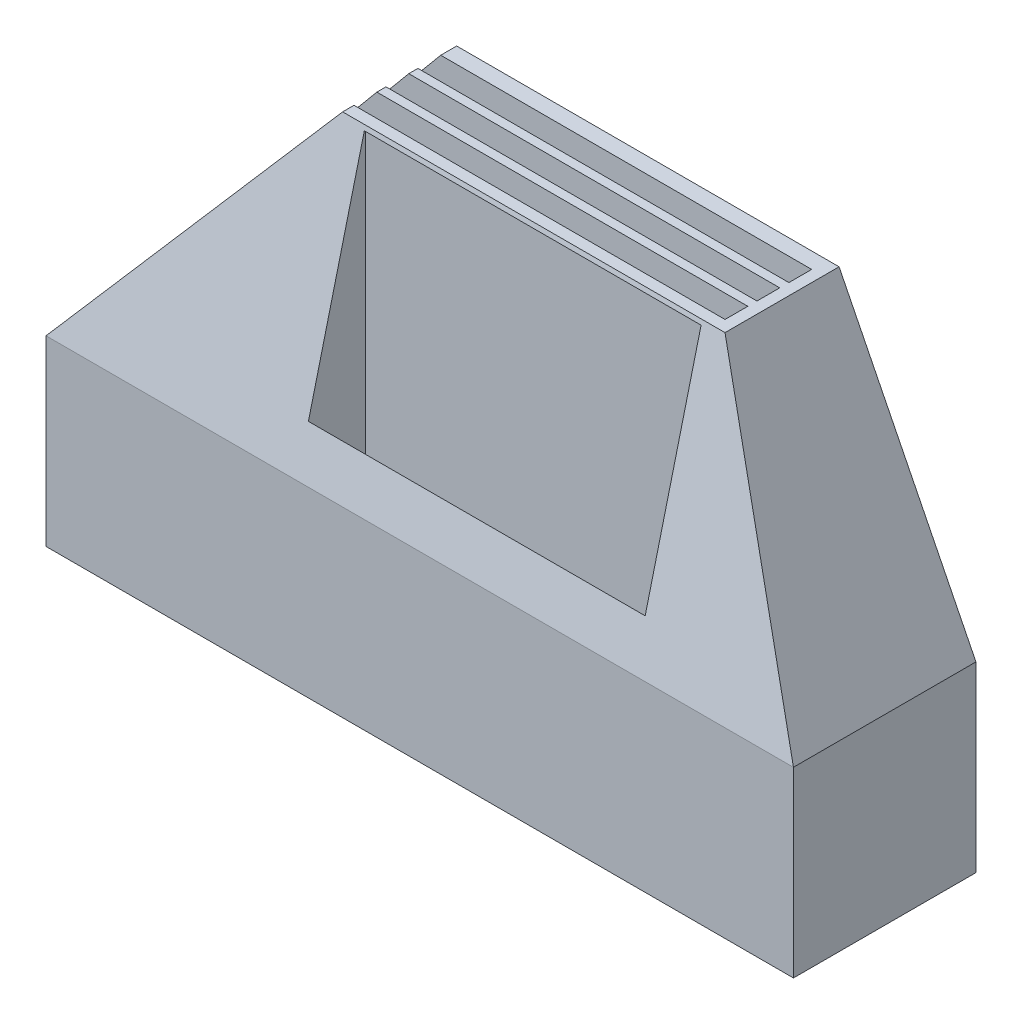
SolidWorks part; units mm, degrees
material "Custom Plastic"
ref_plane "Front Plane" through (0, 0, 0) normal (0, 0, 1) x (1, 0, 0)
ref_plane "Top Plane" through (0, 0, 0) normal (0, 1, 0) x (1, 0, 0)
ref_plane "Right Plane" through (0, 0, 0) normal (1, 0, 0) x (0, 0, -1)
sketch "Sketch1" plane through (0, 0, 0) normal (0, 1, 0) x (1, 0, 0)
  line L1 (0, 0) -> (416.08, 0)
  line L2 (0, 0) -> (0, 101.6)
  line L3 (0, 101.6) -> (416.08, 101.6)
  line L4 (416.08, 0) -> (416.08, 101.6)
  point P5 (416.08, 0)
  point P7 (0, 101.6)
extrude "Boss-Extrude2" add sketch "Sketch1" along normal blind 254
sketch "Sketch2" plane through (0, 0, 0) normal (0, 0, 1) x (1, 0, 0)
  line L0 (0, 101.6) -> (0, 254)
  line L1 (0, 254) -> (0, 0) construction
  line L2 (0, 254) -> (127, 254)
  line L3 (0, 254) -> (416.08, 254) construction
  line L4 (127, 254) -> (0, 101.6)
  line L5 (416.08, 254) -> (416.08, 101.6)
  line L6 (416.08, 254) -> (416.08, 0) construction
  line L7 (416.08, 101.6) -> (339.88, 254)
  line L8 (339.88, 254) -> (416.08, 254)
  dimension "D1" = 152.4
  dimension "D2" = 127
  dimension "D3" = 76.2
extrude "Cut-Extrude1" cut sketch "Sketch2" against normal blind 101.6
sketch "Sketch6" plane through (0, 0, 0) normal (0, 1, 0) x (1, 0, 0)
  line L0 (127, 101.6) -> (127, 0) construction
  line L1 (139.7, 38.1) -> (327.18, 38.1)
  line L2 (139.7, 38.1) -> (139.7, 6.35)
  line L3 (139.7, 6.35) -> (327.18, 6.35)
  line L4 (327.18, 38.1) -> (327.18, 6.35)
  line L5 (139.7, 38.1) -> (327.18, 6.35) construction
  line L6 (139.7, 6.35) -> (327.18, 38.1) construction
  line L7 (416.08, 0) -> (416.08, 101.6) construction
  line L13 (127, 0) -> (339.88, 0) construction
  dimension "D1" = 31.75
  dimension "D2" = 6.35
  dimension "D3" = 12.7
  dimension "D4" = 88.9
extrude "Cut-Extrude9" cut sketch "Sketch6" along normal blind 251.554
sketch "Sketch8" plane through (0, 254, 0) normal (0, 1, 0) x (1, 0, 0)
  line L0 (416.08, 0) -> (416.08, 101.6) construction
  line L1 (6.35, 44.45) -> (333.53, 44.45)
  line L2 (6.35, 44.45) -> (6.35, 57.15)
  line L3 (6.35, 57.15) -> (333.53, 57.15)
  line L4 (333.53, 44.45) -> (333.53, 57.15)
  line L5 (6.35, 44.45) -> (333.53, 57.15) construction
  line L6 (6.35, 57.15) -> (333.53, 44.45) construction
  line L7 (0, 101.6) -> (0, 0) construction
  line L8 (139.7, 38.1) -> (327.18, 38.1) construction
  line L9 (6.35, 62.23) -> (6.35, 74.93)
  line L10 (6.35, 62.23) -> (333.53, 62.23)
  line L11 (333.53, 62.23) -> (333.53, 74.93)
  line L12 (6.35, 74.93) -> (333.53, 74.93)
  line L13 (6.35, 80.01) -> (6.35, 92.71)
  line L14 (6.35, 80.01) -> (333.53, 80.01)
  line L15 (333.53, 80.01) -> (333.53, 92.71)
  line L16 (6.35, 92.71) -> (333.53, 92.71)
  point P0 (169.94, 50.8)
  dimension "D1" = 82.55
  dimension "D2" = 6.35
  dimension "D3" = 6.35
  dimension "D4" = 12.7
  dimension "D5" = 3
extrude "Cut-Extrude11" cut sketch "Sketch8" against normal blind 228.6
sketch "Sketch9" plane through (416.08, 0, 0) normal (1, 0, 0) x (0, 0, -1)
  line L0 (0, 254) -> (0, 101.6)
  line L1 (0, 101.6) -> (38.1, 254)
  line L2 (44.45, 254) -> (0, 254) construction
  line L3 (38.1, 254) -> (0, 254)
  dimension "D1" = 38.1
extrude "Cut-Extrude12" cut sketch "Sketch9" against normal through all
sketch "Sketch10" plane through (0, 0, -38.1) normal (0, 0, 1) x (1, 0, 0)
  line L0 (327.18, 251.554) -> (327.18, 127) construction
  line L1 (314.48, 10.4541) -> (152.4, 10.4541)
  line L2 (314.48, 10.4541) -> (314.48, 23.6587)
  line L3 (314.48, 23.6587) -> (152.4, 23.6587)
  line L4 (152.4, 10.4541) -> (152.4, 23.6587)
  line L5 (139.7, 127) -> (139.7, 251.554) construction
  dimension "D1" = 12.7
  dimension "D2" = 12.7
extrude "Cut-Extrude13" cut sketch "Sketch10" against normal up to next
